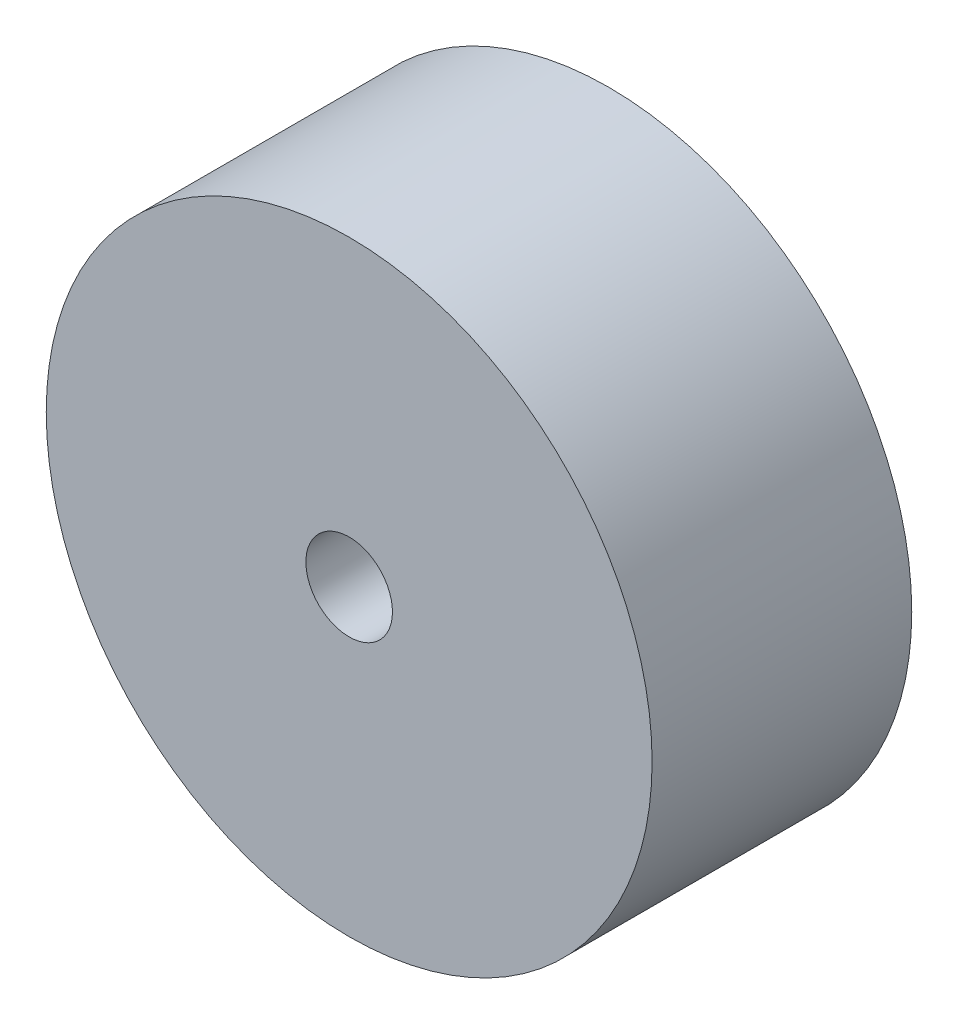
SolidWorks part; units mm, degrees
ref_plane "Front Plane" through (0, 0, 0) normal (0, 0, 1) x (1, 0, 0)
ref_plane "Top Plane" through (0, 0, 0) normal (0, 1, 0) x (1, 0, 0)
ref_plane "Right Plane" through (0, 0, 0) normal (1, 0, 0) x (0, 0, -1)
sketch "Sketch1" plane through (0, 0, 0) normal (0, 0, 1) x (1, 0, 0)
  circle A0 centre (0, 0) radius 35
  dimension "D1" = 70
extrude "Boss-Extrude1" add sketch "Sketch1" against normal blind 30
sketch "Sketch2" plane through (0, 0, 0) normal (0, 0, 1) x (1, 0, 0)
  circle A0 centre (0, 0) radius 5
  dimension "D1" = 10
extrude "Cut-Extrude1" cut sketch "Sketch2" against normal blind 30
